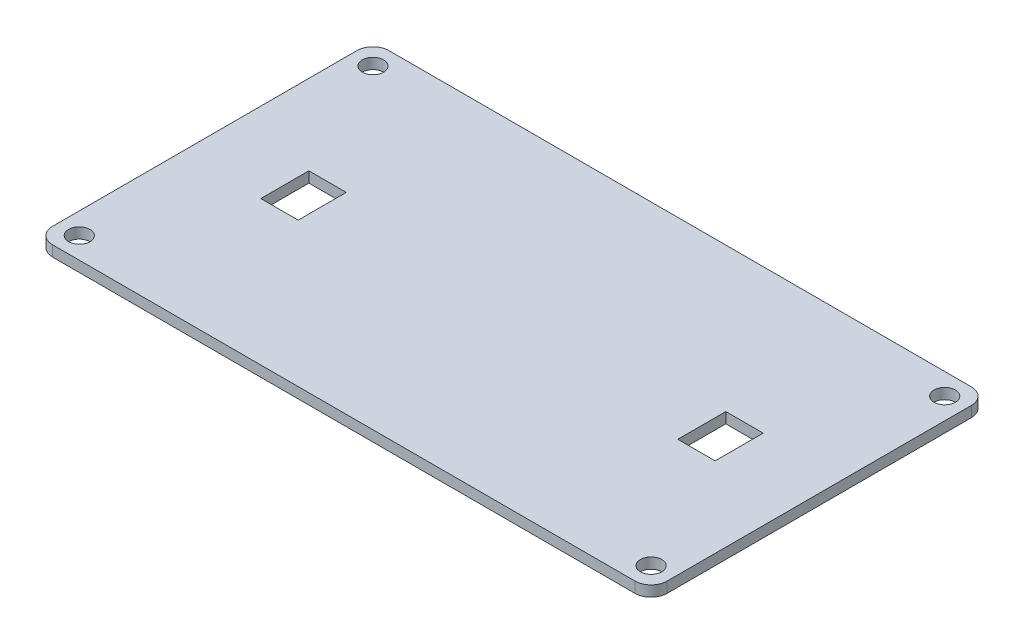
SolidWorks part; units mm, degrees
ref_plane "Plano frontal" through (0, 0, 0) normal (0, 0, 1) x (1, 0, 0)
ref_plane "Plano superior" through (0, 0, 0) normal (0, 1, 0) x (1, 0, 0)
ref_plane "Plano direito" through (0, 0, 0) normal (1, 0, 0) x (0, 0, -1)
sketch "Esboço1" plane through (0, 0, 0) normal (0, 1, 0) x (1, 0, 0)
  line L7 (-57.5484, 31.5) -> (57.5484, 31.5)
  line L8 (57.5484, 31.5) -> (57.5484, -31.5)
  line L9 (57.5484, -31.5) -> (-57.5484, -31.5)
  line L10 (-57.5484, -31.5) -> (-57.5484, 31.5)
  line L11 (0, 31.5) -> (0, -31.5) construction
  line L12 (-57.5484, 0) -> (57.5484, 0) construction
  dimension "D1" = 63
  dimension "D2" = 115.0968
extrude "Ressalto-extrusão1" add sketch "Esboço1" along normal blind 2
sketch "Esboço5" plane through (0, 2, 0) normal (0, 1, 0) x (1, 0, 0)
  line L2 (57.5484, 31.5) -> (-57.5484, 31.5) construction
  line L3 (57.5484, -31.5) -> (57.5484, 31.5) construction
  line L4 (57.5484, 0) -> (-57.5484, 0) construction
  line L5 (-57.5484, 31.5) -> (-57.5484, -31.5) construction
  line L6 (0, 31.5) -> (0, -31.5) construction
  line L7 (-57.5484, -31.5) -> (57.5484, -31.5) construction
  line L8 (53.5484, -13.175) -> (53.5484, -27.5) construction
  line L9 (-53.5484, -13.175) -> (-53.5484, -27.5) construction
  line L10 (-53.5484, 21.175) -> (-53.5484, 35.5) construction
  circle A0 centre (53.5484, 27.5) radius 2
  circle A1 centre (53.5484, -27.5) radius 2
  circle A2 centre (-53.5484, -27.5) radius 2
  circle A3 centre (-53.5484, 27.5) radius 2
  dimension "D2" = 4
  dimension "D1" = 4
  dimension "D3" = 4
extrude "Corte-extrusão3" cut sketch "Esboço5" against normal through all
fillet "Filete1" radius 3 4 edges at (57.5484, 1, -31.5) (57.5484, 1, 31.5) (-57.5484, 1, 31.5) (-57.5484, 1, -31.5)
sketch "Esboço6" plane through (0, 2, 0) normal (0, 1, 0) x (1, 0, 0)
  line L0 (-57.5484, 0) -> (57.5484, 0) construction
  line L1 (-57.5484, 28.5) -> (-57.5484, -28.5) construction
  line L2 (57.5484, -28.5) -> (57.5484, 28.5) construction
  line L3 (-42.5484, -4.5) -> (-42.5484, 4.5)
  line L4 (-42.5484, 4.5) -> (-35.5484, 4.5)
  line L5 (-35.5484, 4.5) -> (-35.5484, -4.5)
  line L6 (-35.5484, -4.5) -> (-42.5484, -4.5)
  line L7 (0, -31.5) -> (0, 31.5) construction
  line L8 (-54.5484, -31.5) -> (54.5484, -31.5) construction
  line L9 (54.5484, 31.5) -> (-54.5484, 31.5) construction
  line L10 (35.5484, -4.5) -> (42.5484, -4.5)
  line L11 (35.5484, 4.5) -> (35.5484, -4.5)
  line L12 (42.5484, 4.5) -> (35.5484, 4.5)
  line L13 (42.5484, -4.5) -> (42.5484, 4.5)
  point P9 (-42.5484, 0)
  point P21 (42.5484, 0)
  dimension "D1" = 9
  dimension "D2" = 7
  dimension "D3" = 15
extrude "Corte-extrusão4" cut sketch "Esboço6" against normal through all and the other way through all
